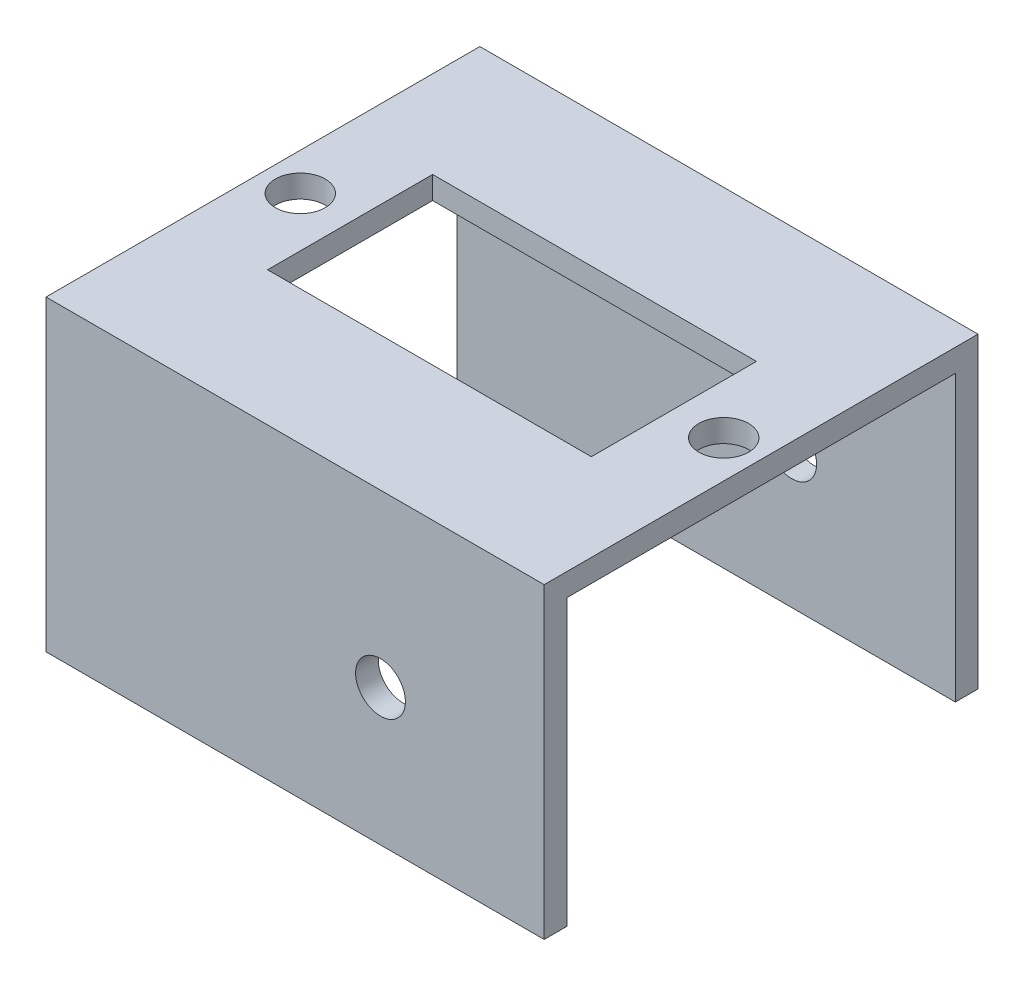
SolidWorks part; units mm, degrees
material "6061 Alloy"
ref_plane "Front Plane" through (0, 0, 0) normal (0, 0, 1) x (1, 0, 0)
ref_plane "Top Plane" through (0, 0, 0) normal (0, 1, 0) x (1, 0, 0)
ref_plane "Right Plane" through (0, 0, 0) normal (1, 0, 0) x (0, 0, -1)
sketch "Sketch1" plane through (0, 0, 0) normal (0, 1, 0) x (1, 0, 0)
  line L0 (-18.1295, 0) -> (18.9836, 0) construction
  line L1 (-22.5, 15.24) -> (22.5, 15.24)
  line L2 (-22.5, 15.24) -> (-22.5, -15.24)
  line L3 (-22.5, -15.24) -> (22.5, -15.24)
  line L4 (22.5, 15.24) -> (22.5, -15.24)
  line L5 (-22.5, 15.24) -> (22.5, -15.24) construction
  line L6 (-22.5, -15.24) -> (22.5, 15.24) construction
  line L7 (-11.375, 5.8) -> (11.375, 5.8)
  line L8 (-11.375, 5.8) -> (-11.375, -5.8)
  line L9 (-11.375, -5.8) -> (11.375, -5.8)
  line L10 (11.375, 5.8) -> (11.375, -5.8)
  line L11 (-11.375, 5.8) -> (11.375, -5.8) construction
  line L12 (-11.375, -5.8) -> (11.375, 5.8) construction
  circle A0 centre (-14.875, 0) radius 1.75
  circle A1 centre (14.875, 0) radius 1.75
  point P0 (0, 0)
  point P6 (0, 0)
  dimension "D7" = 3.5
  dimension "D8" = 3.5
  dimension "D1" = 30.48
  dimension "D2" = 45
  dimension "D3" = 11.6
  dimension "D4" = 22.75
  dimension "D5" = 3.5
  dimension "D6" = 3.5
extrude "Boss-Extrude1" add sketch "Sketch1" along normal blind 1.59
sketch "Sketch2" plane through (0, 0, 0) normal (0, -1, 0) x (1, 0, 0)
  line L0 (22.5, -15.24) -> (-22.5, -15.24) construction
  line L1 (-22.5, 15.24) -> (-20.91, 15.24)
  line L2 (-22.5, 15.24) -> (-22.5, -15.24)
  line L3 (-22.5, -15.24) -> (-20.91, -15.24)
  line L4 (-20.91, 15.24) -> (-20.91, -15.24)
  line L6 (22.5, 15.24) -> (20.91, 15.24)
  line L7 (22.5, 15.24) -> (22.5, -15.24)
  line L8 (22.5, -15.24) -> (20.91, -15.24)
  line L9 (20.91, 15.24) -> (20.91, -15.24)
  dimension "D1" = 1.59
  dimension "D2" = 1.59
extrude "Boss-Extrude2" [suppressed] add sketch "Sketch2" along normal blind 20
sketch "Sketch3" plane through (0, 0, 0) normal (0, -1, 0) x (-1, 0, 0)
  line L0 (22.5, 15.24) -> (22.5, -15.24) construction
  line L1 (22.5, -15.24) -> (-22.5, -15.24)
  line L2 (22.5, -15.24) -> (22.5, -13.65)
  line L3 (22.5, -13.65) -> (-22.5, -13.65)
  line L4 (-22.5, -15.24) -> (-22.5, -13.65)
  line L5 (-22.5, -15.24) -> (-22.5, 15.24) construction
  line L6 (22.5, -15.24) -> (-22.5, -15.24) construction
  line L7 (22.5, 15.24) -> (-22.5, 15.24)
  line L8 (22.5, 15.24) -> (22.5, 13.65)
  line L9 (22.5, 13.65) -> (-22.5, 13.65)
  line L10 (-22.5, 15.24) -> (-22.5, 13.65)
  dimension "D1" = 1.59
  dimension "D2" = 1.59
extrude "Boss-Extrude3" add sketch "Sketch3" along normal blind 20
sketch "Sketch4" plane through (0, 0, 15.24) normal (0, 0, 1) x (1, 0, 0)
  line L0 (-22.5, 1.59) -> (22.5, 1.59) construction
  line L1 (22.5, 1.59) -> (22.5, -20) construction
  circle A0 centre (6, -10.41) radius 1.75
  dimension "D3" = 3.5
  dimension "D1" = 12
  dimension "D2" = 16.5
extrude "Cut-Extrude2" cut sketch "Sketch4" against normal blind 40
sketch "Sketch5" plane through (0, 1.59, 0) normal (0, 1, 0) x (1, 0, 0)
  line L0 (-22.5, -15.24) -> (22.5, -15.24) construction
  line L1 (-22.5, 15.24) -> (-17.5, 15.24)
  line L2 (-22.5, 15.24) -> (-22.5, -15.24)
  line L3 (-22.5, -15.24) -> (-17.5, -15.24)
  line L4 (-17.5, 15.24) -> (-17.5, -15.24)
  line L6 (22.5, 15.24) -> (17.5, 15.24)
  line L7 (22.5, 15.24) -> (22.5, -15.24)
  line L8 (22.5, -15.24) -> (17.5, -15.24)
  line L9 (17.5, 15.24) -> (17.5, -15.24)
  dimension "D1" = 5
  dimension "D2" = 5
extrude "Cut-Extrude3" cut sketch "Sketch5" against normal blind 30
